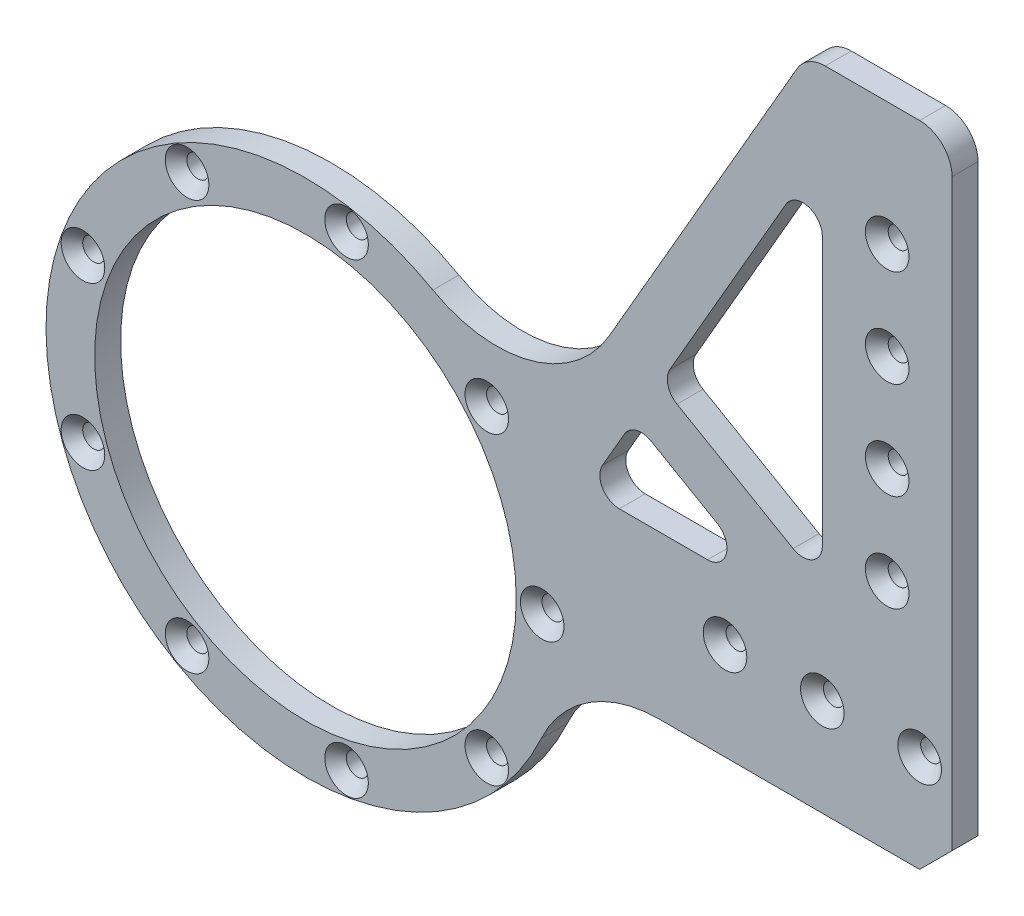
SolidWorks part; units mm, degrees
material "Thornel Mat VMA"
ref_plane "前视基准面" through (0, 0, 0) normal (0, 0, 1) x (1, 0, 0)
ref_plane "上视基准面" through (0, 0, 0) normal (0, 1, 0) x (1, 0, 0)
ref_plane "右视基准面" through (0, 0, 0) normal (1, 0, 0) x (0, 0, -1)
other "Configuration Table"
sketch "草图1" plane through (0, 0, 0) normal (0, 0, 1) x (1, 0, 0)
  circle A0 centre (0, 0) radius 40
  circle A10 centre (0, 0) radius 32.5
  dimension "D1" = 80
  dimension "D6" = 65
extrude "凸台-拉伸1" add sketch "草图1" along normal blind 4
sketch "草图2" plane through (0, 0, 4) normal (0, 0, 1) x (1, 0, 0)
  line L0 (0, 0) -> (40, 0) construction
  line L1 (0, 0) -> (36.5, 0) construction
  circle A0 centre (0, 0) radius 40 construction
  point P6 (36.5, 0)
  point P7 (27.9606, -23.4617)
  point P10 (6.3382, -35.9455)
  point P11 (-18.25, -31.6099)
  point P12 (-34.2988, -12.4837)
  point P13 (-34.2988, 12.4837)
  point P14 (-18.25, 31.6099)
  point P15 (6.3382, 35.9455)
  point P16 (27.9606, 23.4617)
  dimension "D3" = 36.5
  dimension "D2" = 9
hole_wizard "M3 六角凹锥坑螺钉的锥形沉头孔1" positions "草图2" profile "草图3" countersink size "M3" standard "ISO" end condition through all
sketch "草图3" plane through (27.9606, 23.4617, 4) normal (1, 0, 0) x (0, -1, 0)
  line L0 (0, 0) -> (0, 4)
  line L1 (0, 4) -> (1.7, 4)
  line L2 (1.7, 4) -> (1.7, 1.66)
  line L3 (1.7, 1.66) -> (3.36, 0)
  line L5 (3.36, 0) -> (0, 0)
  line L6 (-1.7, 1.66) -> (-3.36, 0) construction
  line L11 (0, -6.35) -> (0, 107.95) construction
  dimension "通孔孔直径" = 3.4
  dimension "通孔孔深度" = 4
  dimension "近端锥形沉头孔直径" = 6.72
  dimension "近端锥形沉头孔角度" = 90
sketch "草图4" plane through (0, 0, 4) normal (0, 0, 1) x (1, 0, 0)
  line L0 (0, 0) -> (40, 0) construction
  line L11 (39.6863, -5) -> (99.6863, -5)
  line L23 (77.2499, 95) -> (99.6863, 95)
  line L26 (99.6863, 95) -> (99.6863, -5)
  line L27 (77.2499, 95) -> (34.2914, 20.5937)
  line L28 (79.6863, 83.2199) -> (43.1863, 20) construction
  line L29 (43.1863, 20) -> (79.6863, 20) construction
  line L30 (79.6863, 20) -> (79.6863, 83.2199) construction
  line L32 (54.6863, 39.9186) -> (79.6863, 25.4848)
  line L33 (50.6863, 32.9904) -> (73.1863, 20)
  line L34 (79.6863, 83.2199) -> (54.6863, 39.9186)
  line L35 (79.6863, 83.2199) -> (79.6863, 25.4848)
  line L36 (50.6863, 32.9904) -> (43.1863, 20)
  line L37 (43.1863, 20) -> (73.1863, 20)
  line L38 (89.6863, 95) -> (89.6863, -5) construction
  circle A0 centre (0, 0) radius 40 construction
  circle A5 centre (79.6863, 10) radius 1.55 construction
  circle A13 centre (94.6863, 10) radius 1.55 construction
  circle A29 centre (64.6863, 10) radius 1.55 construction
  circle A34 centre (89.6863, 76) radius 1.55 construction
  arc A42 (34.2914, 20.5937) -> (39.6863, -5) centre (0, 0) cw
  circle A43 centre (89.6863, 61) radius 1.55 construction
  circle A44 centre (89.6863, 46) radius 1.55 construction
  circle A45 centre (89.6863, 31) radius 1.55 construction
  point P32 (89.6863, 76)
  point P34 (89.6863, 61)
  point P35 (89.6863, 46)
  point P36 (89.6863, 31)
  point P37 (79.6863, 10)
  point P38 (64.6863, 10)
  point P39 (94.6863, 10)
  dimension "D1" = 5
  dimension "D2" = 20
  dimension "D8" = 3.1
  dimension "D9" = 3.1
  dimension "D10" = 15
  dimension "D15" = 15
  dimension "D16" = 15
  dimension "D18" = 10
  dimension "D19" = 3.1
  dimension "D25" = 15
  dimension "D26" = 50
  dimension "D27" = 3.1
  dimension "D6" = 60
  dimension "D11" = 15
  dimension "D3" = 60
  dimension "D14" = 3.1
  dimension "D20" = 3.1
  dimension "D21" = 3.1
  dimension "D4" = 100
  dimension "D5" = 25
  dimension "D7" = 8
  dimension "D12" = 15
  dimension "D13" = 5
  dimension "D17" = 8
  dimension "D22" = 19
  dimension "D23" = 15
  dimension "D24" = 15
  dimension "D28" = 15
extrude "凸台-拉伸2" add sketch "草图4" against normal up to surface (4 mm away) up to face at (38.2, 0, 0)
sketch "草图8" plane through (0, 0, 4) normal (0, 0, 1) x (1, 0, 0)
  line L38 (89.6863, 95) -> (89.6863, -5) construction
  circle A5 centre (79.6863, 10) radius 1.55 construction
  circle A13 centre (94.6863, 10) radius 1.55 construction
  circle A29 centre (64.6863, 10) radius 1.55 construction
  circle A34 centre (89.6863, 76) radius 1.55 construction
  circle A43 centre (89.6863, 61) radius 1.55 construction
  circle A44 centre (89.6863, 46) radius 1.55 construction
  circle A45 centre (89.6863, 31) radius 1.55 construction
  point P32 (89.6863, 76)
  point P34 (89.6863, 61)
  point P35 (89.6863, 46)
  point P36 (89.6863, 31)
  point P37 (79.6863, 10)
  point P38 (64.6863, 10)
  point P39 (94.6863, 10)
  dimension "D8" = 3.1
  dimension "D9" = 3.1
  dimension "D15" = 15
  dimension "D19" = 3.1
  dimension "D27" = 3.1
  dimension "D14" = 3.1
  dimension "D20" = 3.1
  dimension "D21" = 3.1
  dimension "D12" = 15
  dimension "D23" = 15
  dimension "D24" = 15
  dimension "D28" = 15
fillet "圆角1" [suppressed] radius 10
fillet "圆角2" radius 20 2 edges at (39.6863, -5, 2) (34.2914, 20.5937, 2)
fillet "圆角3" [suppressed] radius 20
chamfer "倒角1" distance 5 angle 45 1 edges at (99.6863, -5, 2)
fillet "圆角4" radius 3 6 edges at (43.1863, 20, 2) (50.6863, 32.9904, 2) (73.1863, 20, 2) (54.6863, 39.9186, 2) (79.6863, 83.2199, 2) (79.6863, 25.4848, 2)
fillet "圆角5" radius 5 2 edges at (77.2499, 95, 2) (99.6863, 95, 2)
hole_wizard "M3 六角凹锥坑螺钉的锥形沉头孔3" positions "草图8" profile "草图9" countersink size "M3" standard "ISO" end condition through all
sketch "草图9" plane through (94.6863, 10, 4) normal (1, 0, 0) x (0, -1, 0)
  line L0 (0, 0) -> (0, 4)
  line L1 (0, 4) -> (1.6, 4)
  line L2 (1.6, 4) -> (1.6, 1.76)
  line L3 (1.6, 1.76) -> (3.36, 0)
  line L5 (3.36, 0) -> (0, 0)
  line L6 (-1.6, 1.76) -> (-3.36, 0) construction
  line L11 (0, -6.35) -> (0, 107.95) construction
  dimension "通孔孔直径" = 3.2
  dimension "通孔孔深度" = 4
  dimension "近端锥形沉头孔直径" = 6.72
  dimension "近端锥形沉头孔角度" = 90
